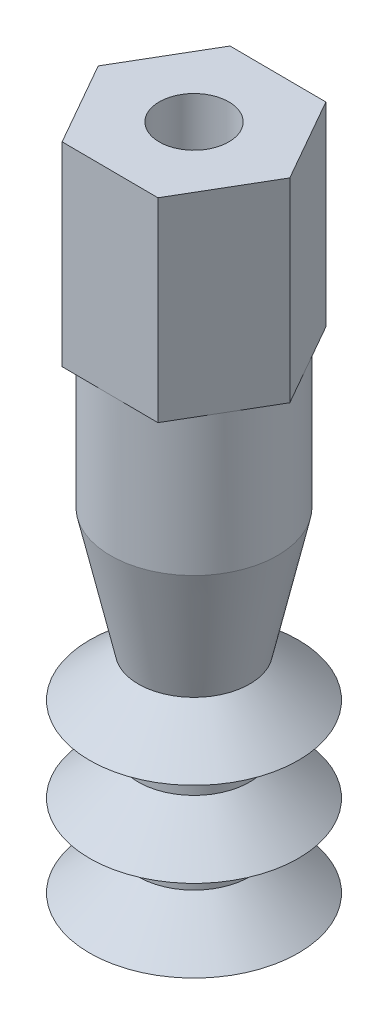
SolidWorks part; units mm, degrees
ref_plane "Front" through (0, 0, 0) normal (0, 0, 1) x (1, 0, 0)
ref_plane "Top" through (0, 0, 0) normal (0, 1, 0) x (1, 0, 0)
ref_plane "Right" through (0, 0, 0) normal (1, 0, 0) x (0, 0, -1)
sketch "esquisse" plane through (0, 0, 0) normal (0, 0, 1) x (1, 0, 0)
  line L0 (0, 0) -> (7.5, 0)
  line L1 (7.5, 0) -> (4, 3)
  line L4 (6, 24) -> (6, 34)
  line L5 (6, 34) -> (0, 34)
  line L6 (0, 34) -> (0, 0)
  line L7 (6, 24) -> (4, 15)
  line L8 (4, 15) -> (7.5, 12)
  line L9 (7.5, 12) -> (4, 12)
  line L10 (4, 12) -> (4, 8.897)
  line L13 (4, 5.897) -> (4, 3)
  line L14 (4, 8.897) -> (7.5, 5.897)
  line L15 (7.5, 5.897) -> (4, 5.897)
  point P4 (6, 20.2499)
  point P12 (6, 20.1519)
  point P14 (3.3371, 17.3887)
  point P15 (4, 8.897)
  point P16 (4, 15.0777)
  point P17 (4, 15)
  dimension "D1" = 10
  dimension "D2" = 34
  dimension "D3" = 7.5
  dimension "D4" = 3
  dimension "D5" = 4
  dimension "D6" = 6
  dimension "D7" = 3
  dimension "D8" = 7.5
  dimension "D9" = 4
  dimension "D10" = 4
  dimension "D11" = 9
  dimension "D12" = 3
  dimension "D13" = 3
  dimension "D14" = 3.103
  dimension "D15" = 7.5
  dimension "D16" = 4
revolve "revolution" add sketch "esquisse" angle 360 about L6
shell "coque" thickness 0.9
sketch "Esboço2" plane through (0, 34, 0) normal (0, 1, 0) x (1, 0, 0)
  line L1 (3.5, 5.9791) -> (-3.4281, 6.0206)
  line L2 (-3.4281, 6.0206) -> (-6.9281, 0.0415)
  line L3 (-6.9281, 0.0415) -> (-3.5, -5.9791)
  line L4 (-3.5, -5.9791) -> (3.4281, -6.0206)
  line L5 (3.4281, -6.0206) -> (6.9281, -0.0415)
  line L6 (6.9281, -0.0415) -> (3.5, 5.9791)
  circle A0 centre (0, 0) radius 6 construction
  dimension "D1" = 12
extrude "bossage" add sketch "Esboço2" along normal blind 14
sketch "esquisse3" plane through (0, 48, 0) normal (0, 1, 0) x (1, 0, 0)
  circle A0 centre (0, 0) radius 2.5
  dimension "D1" = 5
extrude "enlev" cut sketch "esquisse3" against normal through all
